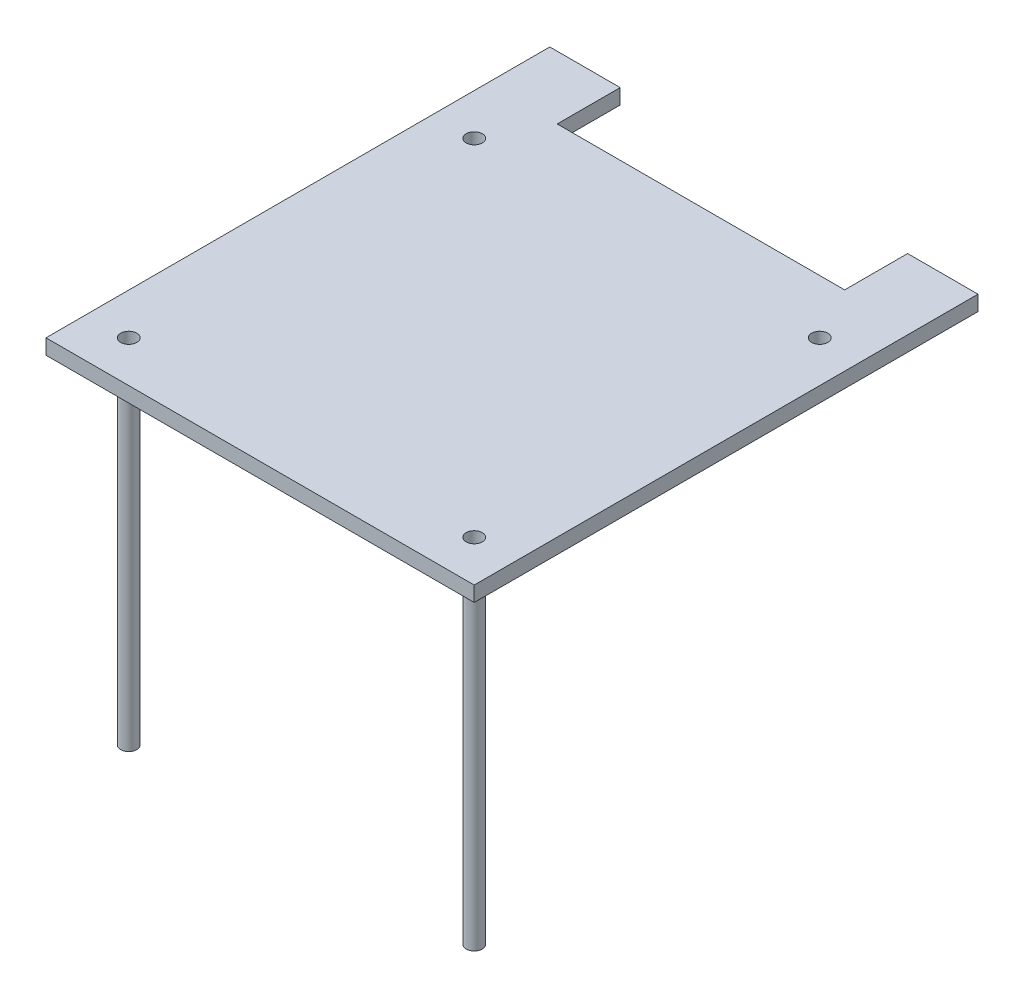
SolidWorks part; units mm, degrees
ref_plane "Front Plane" through (0, 0, 0) normal (0, 0, 1) x (1, 0, 0)
ref_plane "Top Plane" through (0, 0, 0) normal (0, 1, 0) x (1, 0, 0)
ref_plane "Right Plane" through (0, 0, 0) normal (1, 0, 0) x (0, 0, -1)
sketch "Sketch1" plane through (0, 0, 0) normal (0, 1, 0) x (1, 0, 0)
  line L1 (-42.5, -50) -> (42.5, -50)
  line L2 (-42.5, -50) -> (-42.5, 50)
  line L3 (-42.5, 50) -> (42.5, 50)
  line L4 (42.5, -50) -> (42.5, 50)
  line L5 (-42.5, -50) -> (42.5, 50) construction
  line L6 (-42.5, 50) -> (42.5, -50) construction
  point P0 (0, 0)
  dimension "D1" = 85
  dimension "D2" = 100
extrude "Boss-Extrude1" add sketch "Sketch1" along normal blind 3
sketch "Sketch2" plane through (0, 3, 0) normal (0, 1, 0) x (1, 0, 0)
  line L0 (-42.5, -50) -> (42.5, -50) construction
  line L2 (-42.5, 50) -> (-42.5, -50) construction
  line L3 (0, 0) -> (0, 19.361) construction
  circle A0 centre (-34.29, 26.79) radius 1.6
  circle A1 centre (-34.29, -41.79) radius 1.6
  circle A2 centre (34.29, -41.79) radius 1.6
  circle A3 centre (34.29, 26.79) radius 1.6
  dimension "D1" = 68.58
  dimension "D4" = 8.21
  dimension "D6" = 3.2
  dimension "D2" = 3.2
  dimension "D5" = 8.21
extrude "Cut-Extrude1" cut sketch "Sketch2" against normal through all
sketch "Sketch3" plane through (0, 0, 0) normal (0, -1, 0) x (1, 0, 0)
  circle A0 centre (-34.29, 41.79) radius 1.6
  circle A1 centre (34.29, 41.79) radius 1.6
extrude "Boss-Extrude2" add sketch "Sketch3" along normal blind 67 separate body
sketch "Sketch4" plane through (0, 3, 0) normal (0, 1, 0) x (1, 0, 0)
  line L0 (42.5, 50) -> (-42.5, 50) construction
  line L1 (-28.5284, 62.5) -> (28.5284, 62.5)
  line L2 (-28.5284, 62.5) -> (-28.5284, 37.5)
  line L3 (-28.5284, 37.5) -> (28.5284, 37.5)
  line L4 (28.5284, 62.5) -> (28.5284, 37.5)
  line L5 (-28.5284, 62.5) -> (28.5284, 37.5) construction
  line L6 (-28.5284, 37.5) -> (28.5284, 62.5) construction
  point P0 (0, 50)
  dimension "D1" = 25
extrude "Cut-Extrude2" cut sketch "Sketch4" against normal through all
